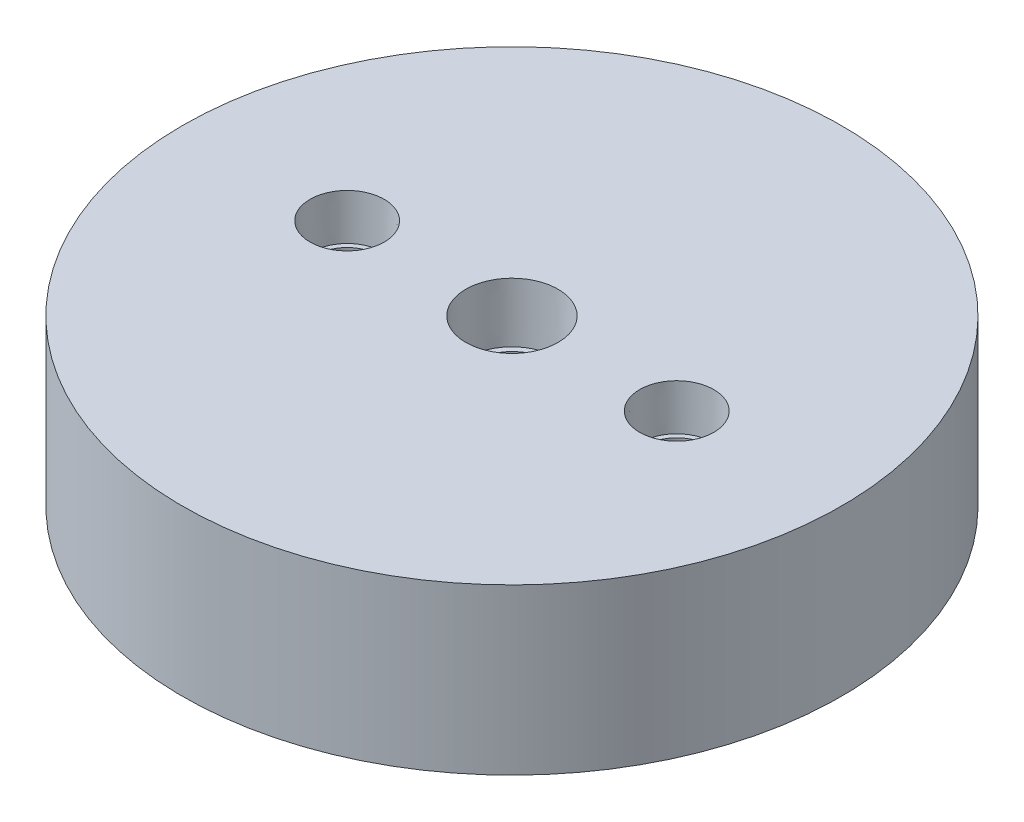
SolidWorks part; units mm, degrees
ref_plane "Front Plane" through (0, 0, 0) normal (0, 0, 1) x (1, 0, 0)
ref_plane "Top Plane" through (0, 0, 0) normal (0, 1, 0) x (1, 0, 0)
ref_plane "Right Plane" through (0, 0, 0) normal (1, 0, 0) x (0, 0, -1)
sketch "Sketch1" plane through (0, 0, 0) normal (0, 0, 1) x (1, 0, 0)
  line L0 (0, 0) -> (-76.2, 0)
  line L1 (-76.2, 0) -> (-76.2, -38.1)
  line L2 (-76.2, -38.1) -> (-60.96, -38.1)
  line L3 (-60.96, -38.1) -> (-60.96, -25.4)
  line L4 (-60.96, -25.4) -> (-28.575, -25.4)
  line L5 (0, 0) -> (0, -15.8572)
  line L8 (-28.575, -25.4) -> (-28.575, -20.32)
  line L9 (-28.575, -20.32) -> (-22.225, -20.32)
  line L10 (-22.225, -20.32) -> (0, -15.8572)
  dimension "D1" = 76.2
  dimension "D2" = 38.1
  dimension "D3" = 15.24
  dimension "D4" = 12.7
  dimension "D5" = 32.385
  dimension "D6" = 15.8572
  dimension "D7" = 6.35
  dimension "D8" = 5.08
revolve "Revolve1" add sketch "Sketch1" angle 360 about L5
hole_wizard "1/2 NPT Tapped Hole1" positions "Sketch2" profile "Sketch3" size "1/2" standard "ANSI Inch" end condition through all
sketch "Sketch2" plane through (0, 0, 0) normal (0, 1, 0) x (1, 0, 0)
  point P0 (0, 0)
sketch "Sketch3" plane through (0, 0, 0) normal (1, 0, 0) x (0, 0, 1)
  line L0 (0, 0) -> (0, 38.1)
  line L1 (0, 38.1) -> (8.9281, 38.1)
  line L2 (-10.2617, 13.462) -> (-10.6647, 0) construction
  line L3 (8.9281, 38.1) -> (8.9281, 13.462)
  line L4 (8.9281, 13.462) -> (10.2617, 13.462)
  line L5 (10.2617, 13.462) -> (10.6647, 0)
  line L7 (10.6647, 0) -> (0, 0)
  line L8 (0, -6.35) -> (0, 107.95) construction
  line L11 (-8.9281, 13.462) -> (-10.2617, 13.462) construction
  dimension "Thru Tap Drill Dia." = 17.8562
  dimension "Thru Tap Drill Depth" = 38.1
  dimension "Thread Dia." = 21.3295
  dimension "Thread Angle" = 3.43
  dimension "Thread Depth" = 13.462
hole_wizard "3/8 NPT Tapped Hole1" positions "Sketch4" profile "Sketch5" size "3/8" standard "ANSI Inch" end condition through all
sketch "Sketch4" plane through (0, 0, 0) normal (0, 1, 0) x (1, 0, 0)
  point P0 (-38.1, 0)
  point P2 (38.1, 0)
  dimension "D1" = 38.1
  dimension "D2" = 38.1
sketch "Sketch5" plane through (-38.1, 0, 0) normal (1, 0, 0) x (0, 0, 1)
  line L0 (0, 0) -> (0, 38.1)
  line L1 (0, 38.1) -> (7.1374, 38.1)
  line L2 (-8.2632, 10.414) -> (-8.575, 0) construction
  line L3 (7.1374, 38.1) -> (7.1374, 10.414)
  line L4 (7.1374, 10.414) -> (8.2632, 10.414)
  line L5 (8.2632, 10.414) -> (8.575, 0)
  line L7 (8.575, 0) -> (0, 0)
  line L8 (0, -6.35) -> (0, 107.95) construction
  line L11 (-7.1374, 10.414) -> (-8.2632, 10.414) construction
  dimension "Thru Tap Drill Dia." = 14.2748
  dimension "Thru Tap Drill Depth" = 38.1
  dimension "Thread Dia." = 17.15
  dimension "Thread Angle" = 3.43
  dimension "Thread Depth" = 10.414
